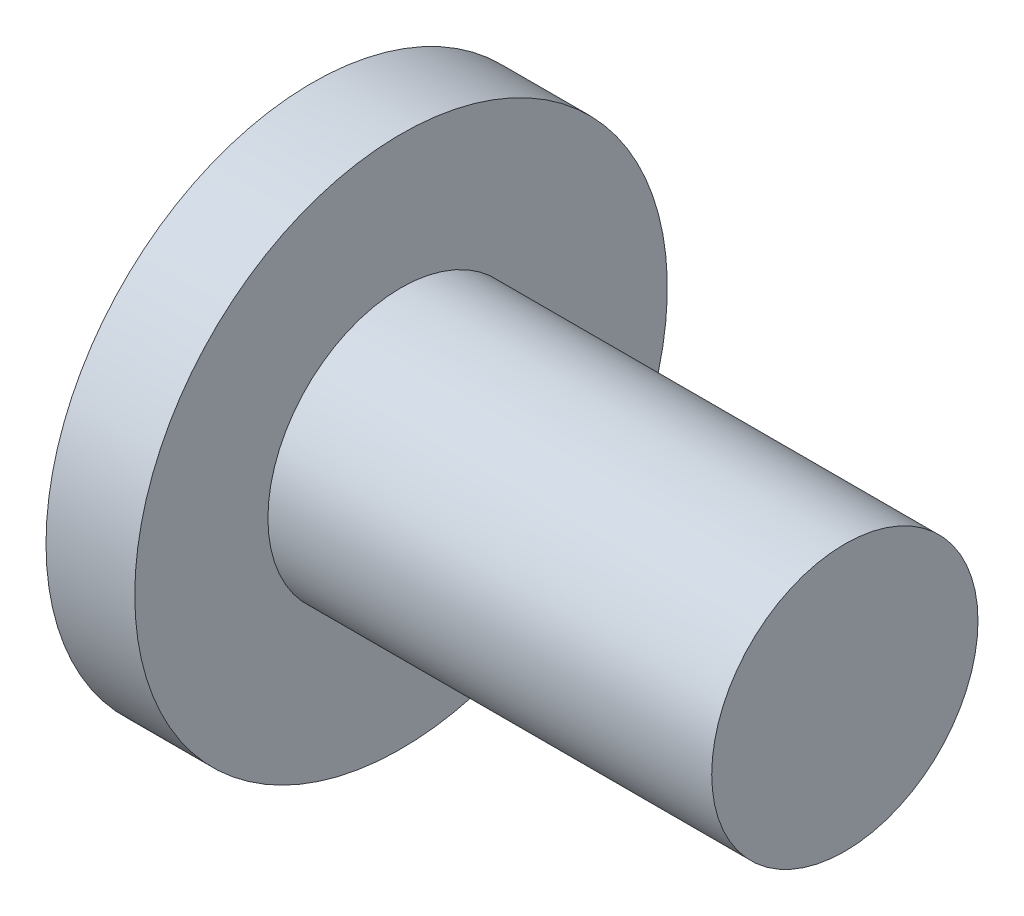
SolidWorks part; units mm, degrees
ref_plane "Front Plane" through (0, 0, 0) normal (0, 0, 1) x (1, 0, 0)
ref_plane "Top Plane" through (0, 0, 0) normal (0, 1, 0) x (1, 0, 0)
ref_plane "Right Plane" through (0, 0, 0) normal (1, 0, 0) x (0, 0, -1)
sketch "Sketch1" plane through (0, 0, 0) normal (0, 1, 0) x (1, 0, 0)
  line L0 (0, 0) -> (12, 0)
  line L1 (12, 0) -> (12, 3)
  line L2 (12, 3) -> (2, 3)
  line L3 (2, 3) -> (2, 6)
  line L4 (2, 6) -> (0, 6)
  line L5 (0, 6) -> (0, 0)
  dimension "D1" = 12
  dimension "D2" = 3
  dimension "D3" = 10
  dimension "D4" = 3
  dimension "D5" = 2
revolve "Revolve1" add sketch "Sketch1" angle 360 about L0
